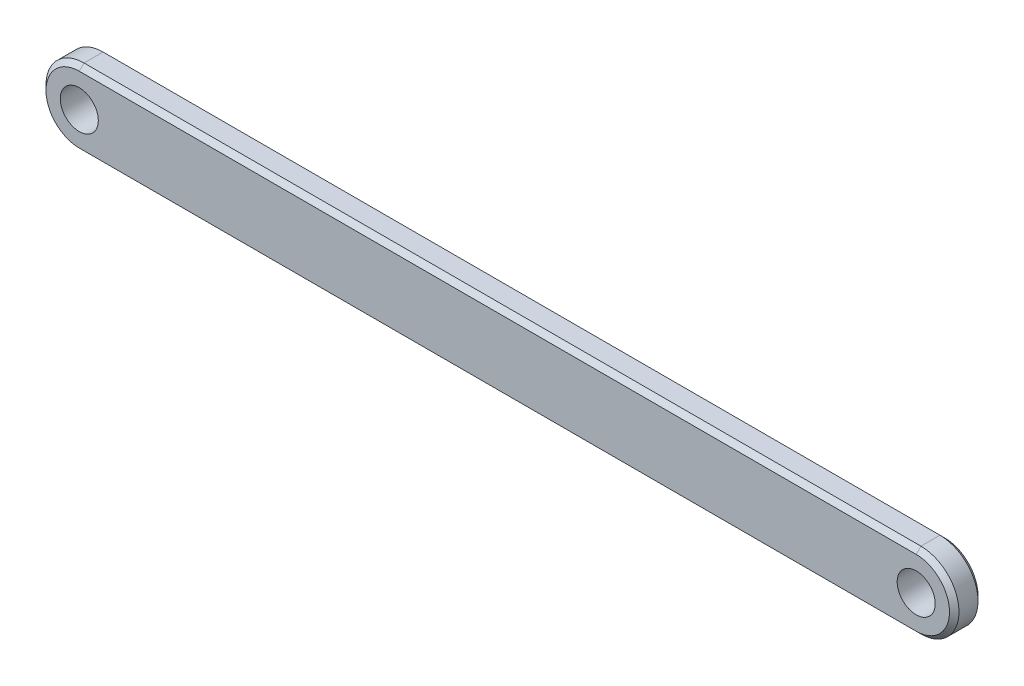
SolidWorks part; units mm, degrees
ref_plane "Front Plane" through (0, 0, 0) normal (0, 0, 1) x (1, 0, 0)
ref_plane "Top Plane" through (0, 0, 0) normal (0, 1, 0) x (1, 0, 0)
ref_plane "Right Plane" through (0, 0, 0) normal (1, 0, 0) x (0, 0, -1)
sketch "Sketch1" plane through (0, 0, 0) normal (0, 0, 1) x (1, 0, 0)
  line L0 (44, 0) -> (-44, 0) construction
  line L1 (44, -4) -> (-44, -4)
  line L2 (44, 4) -> (-44, 4)
  arc A0 (44, -4) -> (44, 4) centre (44, 0) ccw
  arc A1 (-44, 4) -> (-44, -4) centre (-44, 0) ccw
  circle A2 centre (-44, 0) radius 2
  circle A3 centre (44, 0) radius 2
  point P2 (0, 0)
  dimension "D2" = 4
  dimension "D3" = 4
  dimension "D4" = 4
  dimension "D1" = 88
extrude "Boss-Extrude1" add sketch "Sketch1" along normal mid plane 3
chamfer "Chamfer1" distance 0.5 angle 45 8 edges at (48, 0, 1.5) (48, 0, -1.5) (0, 4, -1.5) (0, -4, -1.5) (-48, 0, -1.5) (0, 4, 1.5) (0, -4, 1.5) (-48, 0, 1.5)
